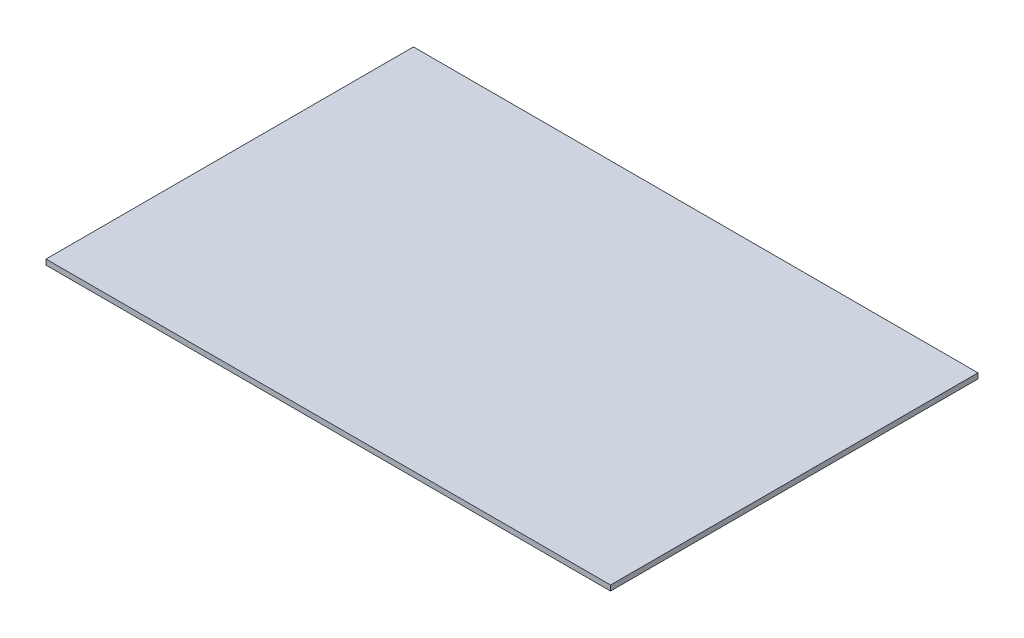
SolidWorks part; units mm, degrees
ref_plane "前视基准面" through (0, 0, 0) normal (0, 0, 1) x (1, 0, 0)
ref_plane "上视基准面" through (0, 0, 0) normal (0, 1, 0) x (1, 0, 0)
ref_plane "右视基准面" through (0, 0, 0) normal (1, 0, 0) x (0, 0, -1)
sketch "草图1" plane through (0, 0, 0) normal (0, 1, 0) x (1, 0, 0)
  line L1 (-160, 104.14) -> (160, 104.14)
  line L2 (-160, 104.14) -> (-160, -104.14)
  line L3 (-160, -104.14) -> (160, -104.14)
  line L4 (160, 104.14) -> (160, -104.14)
  line L5 (-160, 104.14) -> (160, -104.14) construction
  line L6 (-160, -104.14) -> (160, 104.14) construction
  point P0 (0, 0)
  dimension "D1" = 320
  dimension "D2" = 208.28
extrude "凸台-拉伸1" add sketch "草图1" along normal blind 3
